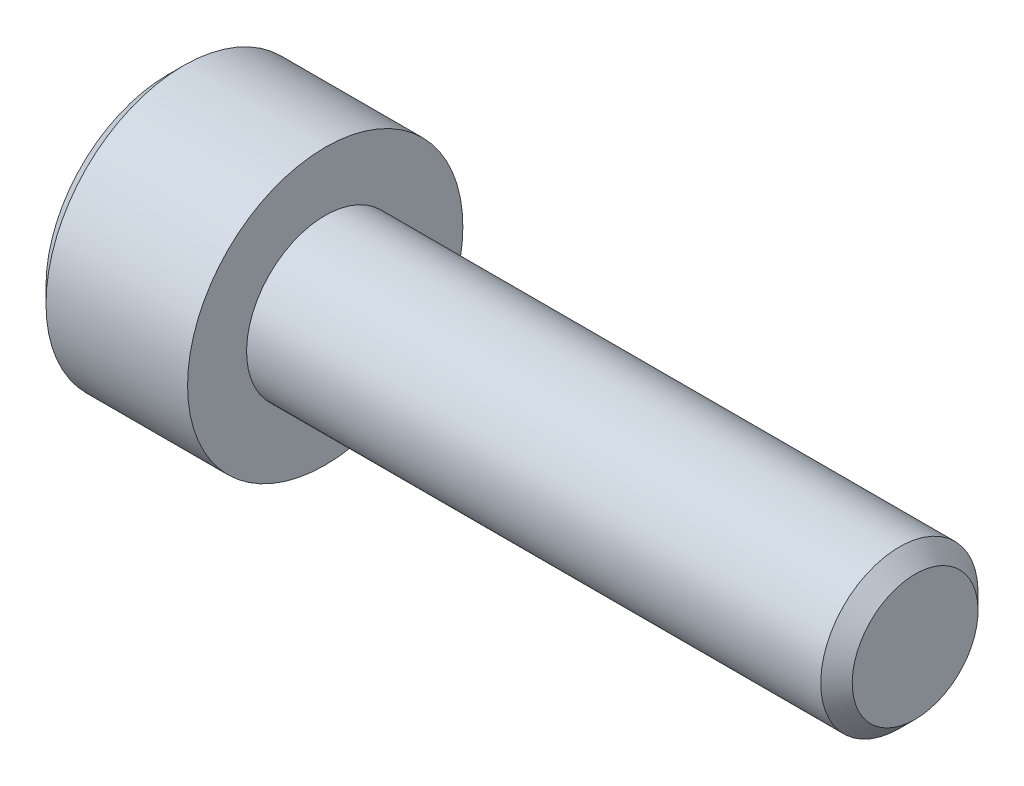
SolidWorks part; units mm, degrees
ref_plane "Front" through (0, 0, 0) normal (0, 0, 1) x (1, 0, 0)
ref_plane "Top" through (0, 0, 0) normal (0, 1, 0) x (1, 0, 0)
ref_plane "Right" through (0, 0, 0) normal (1, 0, 0) x (0, 0, -1)
ref_plane "Plane1" through (0, 0, 0) normal (0, 0, 1) x (1, 0, 0)
sketch "Sketch1" plane through (0, 0, 0) normal (0, 0, 1) x (1, 0, 0)
  line L0 (-4, 0) -> (-4, 3.1)
  line L1 (-4, 3.1) -> (-3.6, 3.5)
  line L2 (-3.6, 3.5) -> (0, 3.5)
  line L3 (0, 3.5) -> (0, 2)
  line L4 (0, 2) -> (15, 2)
  line L6 (15, 2) -> (15, 0)
  line L7 (15, 0) -> (-4, 0)
  line L8 (15, 0) -> (-4, 0) construction
  dimension "D1" = 15
  dimension "D2" = 4
  dimension "D3" = 2
  dimension "D4" = 3.5
revolve "Revolve1" add sketch "Sketch1" angle 360 about L8
ref_plane "Plane2" through (0, 0, 0) normal (0, 0, 1) x (1, 0, 0)
chamfer "Chamfer1" distance 0.4 angle 45 1 edges at (15, -2, 0)
sketch "Sketch2" plane through (0, 0, 0) normal (0, 0, 1) x (1, 0, 0)
  line L0 (-4, 0) -> (-4, 1.5)
  line L1 (-4, 1.5) -> (-2, 1.5)
  line L2 (-2, 1.5) -> (-1.5981, 0)
  line L3 (-1.5981, 0) -> (-4, 0)
  line L4 (-1.5981, 0) -> (-4, 0) construction
revolve "Cut-Revolve1" cut sketch "Sketch2" angle 360 about L4
ref_plane "Plane3" through (-4, 0, 0) normal (1, 0, 0) x (0, 0, -1)
sketch "Sketch3" plane through (-4, 0, 0) normal (1, 0, 0) x (0, 0, -1)
  line L0 (-1.5, 0.866) -> (-1.5, -0.866)
  line L1 (-1.5, -0.866) -> (0, -1.7321)
  line L2 (0, -1.7321) -> (1.5, -0.866)
  line L3 (1.5, -0.866) -> (1.5, 0.866)
  line L4 (1.5, 0.866) -> (0, 1.7321)
  line L5 (0, 1.7321) -> (-1.5, 0.866)
extrude "Cut-Extrude1" cut sketch "Sketch3" along normal blind 2
